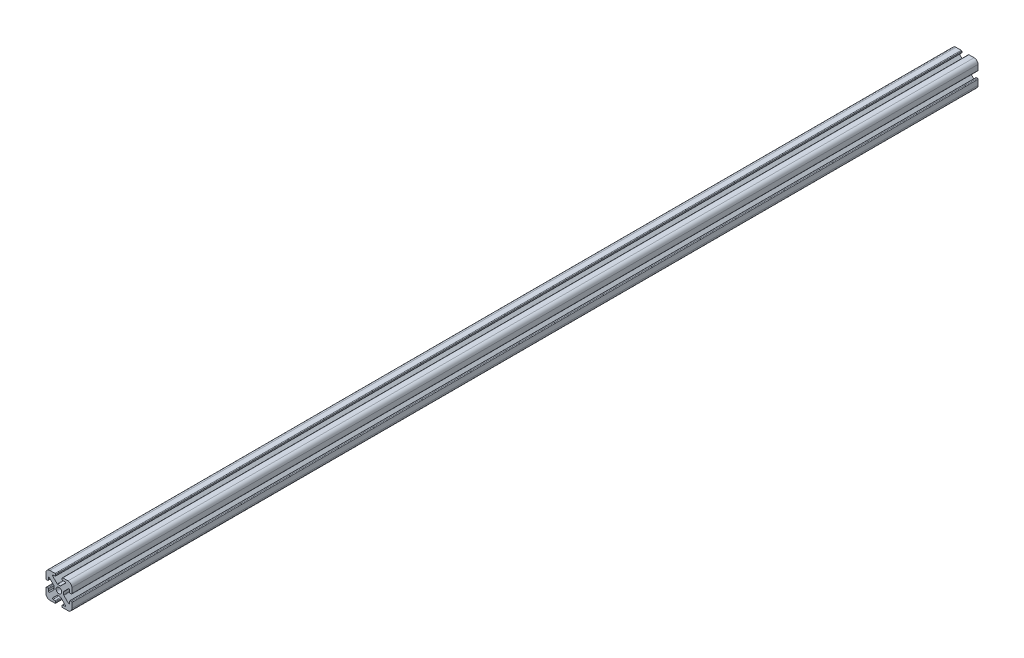
SolidWorks part; units mm, degrees
ref_plane "Front Plane" through (0, 0, 0) normal (0, 0, 1) x (1, 0, 0)
ref_plane "Top Plane" through (0, 0, 0) normal (0, 1, 0) x (1, 0, 0)
ref_plane "Right Plane" through (0, 0, 0) normal (1, 0, 0) x (0, 0, -1)
sketch "Sketch1" plane through (0, 0, 0) normal (0, 0, 1) x (1, 0, 0)
  line L1 (-3.65, 3.65) -> (3.65, 3.65)
  line L2 (-3.65, 3.65) -> (-3.65, -3.65)
  line L3 (-3.65, -3.65) -> (3.65, -3.65)
  line L4 (3.65, 3.65) -> (3.65, -3.65)
  line L5 (-3.65, 3.65) -> (3.65, -3.65) construction
  line L6 (-3.65, -3.65) -> (3.65, 3.65) construction
  circle A0 centre (0, 0) radius 2.15
  point P0 (0, 0)
  dimension "D1" = 7.3
  dimension "D2" = 7.3
extrude "Boss-Extrude1" add sketch "Sketch1" along normal blind 700
sketch "Sketch2" plane through (0, 0, 0) normal (0, 0, 1) x (1, 0, 0)
  line L0 (3.65, 3.65) -> (1.2, 3.65)
  line L1 (3.65, 3.65) -> (-3.65, 3.65) construction
  line L2 (3.65, -3.65) -> (3.65, 3.65) construction
  line L4 (3.65, 3.65) -> (3.65, 1.2)
  line L5 (1.2, 3.65) -> (5.75, 8.2)
  line L6 (3.65, 1.2) -> (8.2, 5.75)
  line L7 (8.2, 5.75) -> (8.2, 2.5)
  line L8 (5.75, 8.2) -> (2.5, 8.2)
  line L9 (8.2, 2.5) -> (10, 2.5)
  line L10 (2.5, 8.2) -> (2.5, 10)
  line L11 (2.5, 10) -> (10, 10)
  line L12 (10, 2.5) -> (10, 10)
  line L13 (-3.65, 3.65) -> (-1.2, 3.65)
  line L14 (-3.65, 3.65) -> (-3.65, 1.2)
  line L15 (-3.65, 3.65) -> (-3.65, -3.65) construction
  line L16 (-3.65, -3.65) -> (-3.65, -1.2)
  line L17 (-3.65, -3.65) -> (-1.2, -3.65)
  line L18 (-3.65, -3.65) -> (3.65, -3.65) construction
  line L19 (3.65, -3.65) -> (3.65, -1.2)
  line L20 (3.65, -3.65) -> (1.2, -3.65)
  line L21 (-3.65, -1.2) -> (-8.2, -5.75)
  line L22 (-1.2, -3.65) -> (-5.75, -8.2)
  line L23 (3.65, -1.2) -> (8.2, -5.75)
  line L24 (1.2, -3.65) -> (5.75, -8.2)
  line L25 (-1.2, 3.65) -> (-5.75, 8.2)
  line L26 (-3.65, 1.2) -> (-8.2, 5.75)
  line L27 (-5.75, 8.2) -> (-2.5, 8.2)
  line L28 (-8.2, 5.75) -> (-8.2, 2.5)
  line L29 (8.2, -5.75) -> (8.2, -2.5)
  line L30 (5.75, -8.2) -> (2.5, -8.2)
  line L31 (-5.75, -8.2) -> (-2.5, -8.2)
  line L32 (-8.2, -5.75) -> (-8.2, -2.5)
  line L33 (8.2, -2.5) -> (10, -2.5)
  line L34 (2.5, -8.2) -> (2.5, -10)
  line L35 (-2.5, -8.2) -> (-2.5, -10)
  line L36 (-8.2, -2.5) -> (-10, -2.5)
  line L37 (-8.2, 2.5) -> (-10, 2.5)
  line L38 (-2.5, 8.2) -> (-2.5, 10)
  line L39 (-2.5, 10) -> (-10, 10)
  line L40 (-10, 10) -> (-10, 2.5)
  line L41 (-10, -2.5) -> (-10, -10)
  line L42 (-10, -10) -> (-2.5, -10)
  line L43 (2.5, -10) -> (10, -10)
  line L44 (10, -10) -> (10, -2.5)
extrude "Boss-Extrude2" add sketch "Sketch2" along normal blind 700
fillet "Fillet4" radius 3 4 edges at (-10, -10, 350) (-10, 10, 350) (10, 10, 350) (10, -10, 350)
fillet "Fillet5" radius 0.5 15 edges at (2.5, 10, 350) (2.5, 8.2, 350) (-2.5, 10, 350) (-2.5, 8.2, 350) (8.2, 2.5, 350) (-8.2, 2.5, 350) (10, 2.5, 350) (-8.2, -2.5, 350) (-2.5, -10, 350) (-2.5, -8.2, 350) (-10, 2.5, 350) (-10, -2.5, 350) (10, -2.5, 350) (8.2, -2.5, 350) (2.5, -8.2, 350)
fillet "Fillet6" radius 0.5 8 edges at (1.2, -3.65, 350) (-1.2, -3.65, 350) (3.65, -1.2, 350) (3.65, 1.2, 350) (-1.2, 3.65, 350) (1.2, 3.65, 350) (-3.65, -1.2, 350) (-3.65, 1.2, 350)
fillet "Fillet7" radius 0.5 8 edges at (8.2, -5.75, 350) (8.2, 5.75, 350) (-8.2, -5.75, 350) (5.75, 8.2, 350) (-5.75, -8.2, 350) (5.75, -8.2, 350) (-8.2, 5.75, 350) (-5.75, 8.2, 350)
sketch "Sketch3" plane through (-3.65, 0, 0) normal (-1, 0, 0) x (0, 0, 1)
  line L0 (0, 0) -> (10, 0) construction
  circle A0 centre (10, 0) radius 2.15
  dimension "D1" = 10
extrude "Cut-Extrude1" cut sketch "Sketch3" against normal through all
sketch "Sketch4" plane through (3.65, 0, 0) normal (1, 0, 0) x (0, 0, -1)
  line L0 (0, 0) -> (-10, 0) construction
  line L1 (0, -0.9929) -> (0, 0.9929) construction
  circle A0 centre (-10, 0) radius 2.15
extrude "Cut-Extrude2" cut sketch "Sketch4" against normal through all
sketch "Sketch5" plane through (3.65, 0, 0) normal (1, 0, 0) x (0, 0, -1)
  line L0 (-700, 0) -> (-690, 0) construction
  line L1 (-700, -0.9929) -> (-700, 0.9929) construction
  circle A0 centre (-690, 0) radius 2.15
  dimension "D1" = 10
extrude "Cut-Extrude3" cut sketch "Sketch5" against normal through all
sketch "Sketch6" plane through (-3.65, 0, 0) normal (-1, 0, 0) x (0, 0, 1)
  line L0 (700, 0) -> (690, 0) construction
  line L1 (700, 0.9929) -> (700, -0.9929) construction
  circle A0 centre (690, 0) radius 2.15
extrude "Cut-Extrude4" cut sketch "Sketch6" against normal through all
sketch "Sketch7" plane through (-3.65, 0, 0) normal (-1, 0, 0) x (0, 0, 1)
